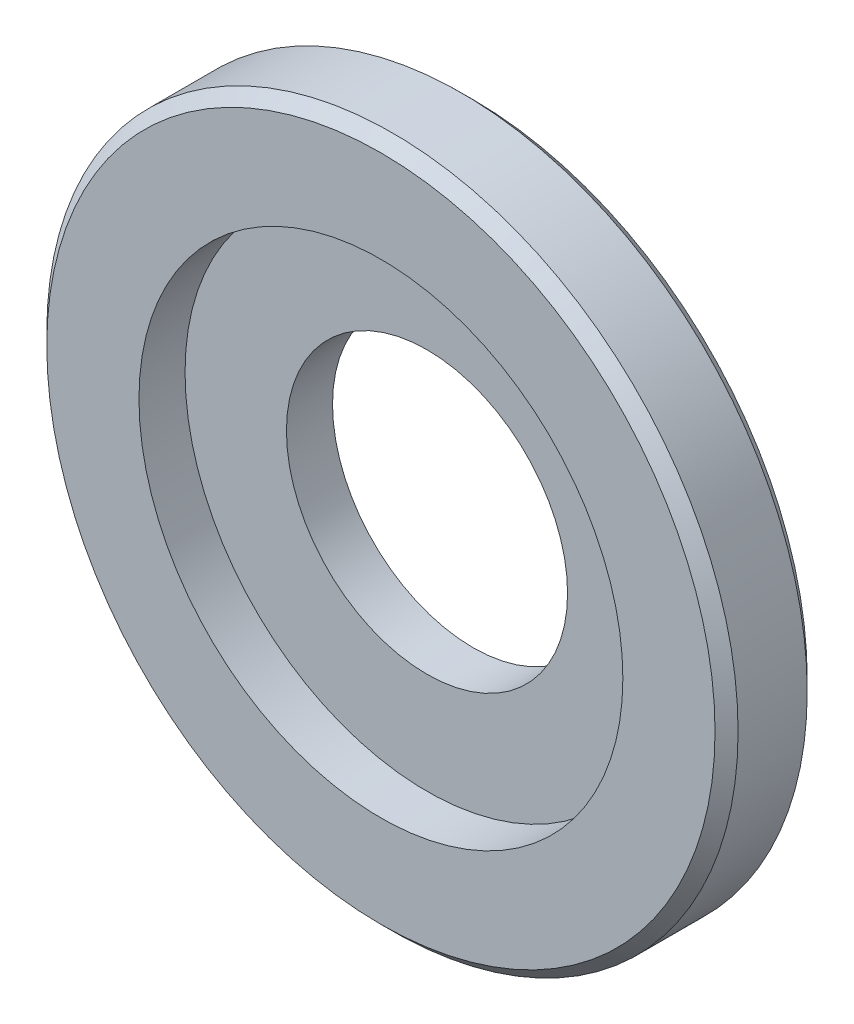
SolidWorks part; units mm, degrees
material "AISI 1020"
ref_plane "Face" through (0, 0, 0) normal (0, 0, 1) x (1, 0, 0)
ref_plane "Dessus" through (0, 0, 0) normal (0, 1, 0) x (1, 0, 0)
ref_plane "Droite" through (0, 0, 0) normal (1, 0, 0) x (0, 0, -1)
sketch "Esquisse1" plane through (0, 0, 0) normal (0, 0, 1) x (1, 0, 0)
  circle A0 centre (0, 0) radius 6.1
  circle A1 centre (0, 0) radius 15
  dimension "D1" = 12.2
  dimension "D2" = 30
extrude "Boss.-Extru.1" add sketch "Esquisse1" along normal blind 4
sketch "Esquisse2" plane through (0, 0, 4) normal (0, 0, 1) x (1, 0, 0)
  circle A0 centre (0, 0) radius 10.5
  dimension "D1" = 21
extrude "Enlèv. mat.-Extru.1" cut sketch "Esquisse2" against normal blind 2
chamfer "Chanfrein1" distance 0.5 angle 45 2 edges at (15, 0, 0) (15, 0, 4)
